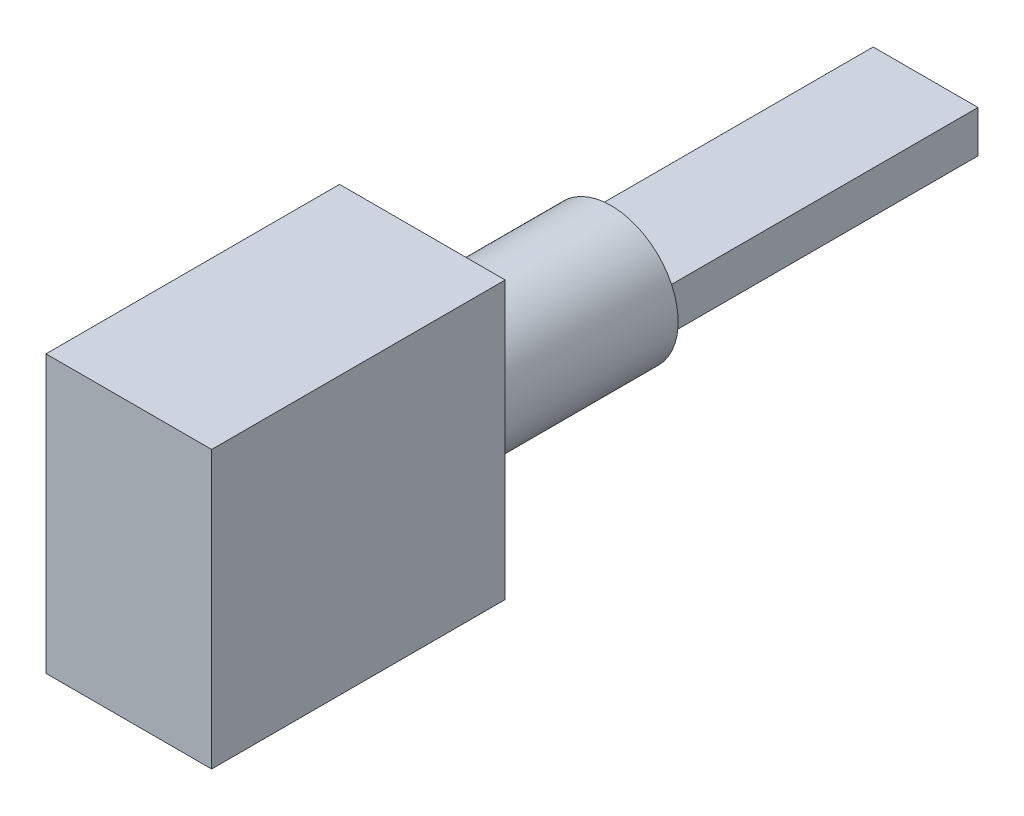
SolidWorks part; units mm, degrees
ref_plane "前基準面" through (0, 0, 0) normal (0, 0, 1) x (1, 0, 0)
ref_plane "上基準面" through (0, 0, 0) normal (0, 1, 0) x (1, 0, 0)
ref_plane "右基準面" through (0, 0, 0) normal (1, 0, 0) x (0, 0, -1)
sketch "草圖1" plane through (0, 0, 0) normal (0, 0, 1) x (1, 0, 0)
  line L0 (-43.8655, -29.1074) -> (43.7345, -29.1074) construction
  line L1 (-24.6655, -72.3074) -> (-32.5655, -72.3074)
  line L2 (-24.6655, -72.3074) -> (-24.6655, -59.1074)
  line L3 (-24.6655, -59.1074) -> (-32.5655, -59.1074)
  line L4 (-32.5655, -72.3074) -> (-32.5655, -59.1074)
  line L5 (-44.5655, -42.9237) -> (-44.5655, -29.8074) construction
  point P6 (-32.5655, -65.7074)
  dimension "D1" = 7.9
  dimension "D2" = 13.2
  dimension "D3" = 30
  dimension "D4" = 12
extrude "填料-伸長1" add sketch "草圖1" along normal blind 14
sketch "草圖2" plane through (0, 0, 0) normal (0, 0, -1) x (-1, 0, 0)
  line L0 (32.5655, -59.1074) -> (32.5655, -72.3074) construction
  line L1 (24.6655, -59.1074) -> (32.5655, -59.1074) construction
  line L2 (24.6655, -72.3074) -> (24.6655, -59.1074) construction
  circle A0 centre (28.6155, -65.7074) radius 3.2
  dimension "D1" = 6.4
  dimension "D2" = 3.95
  dimension "D3" = 6.6
  dimension "D4" = 3.95
extrude "填料-伸長2" add sketch "草圖2" along normal blind 9
sketch "草圖3" plane through (0, 0, -9) normal (0, 0, -1) x (-1, 0, 0)
  line L0 (24.6655, -72.3074) -> (24.6655, -59.1074) construction
  line L1 (26.1155, -64.7074) -> (31.1155, -64.7074)
  line L2 (26.1155, -64.7074) -> (26.1155, -66.7074)
  line L3 (26.1155, -66.7074) -> (31.1155, -66.7074)
  line L4 (31.1155, -64.7074) -> (31.1155, -66.7074)
  line L5 (24.6655, -59.1074) -> (32.5655, -59.1074) construction
  point P4 (28.6155, -64.7074)
  point P7 (31.1155, -65.7074)
  dimension "D1" = 3.95
  dimension "D2" = 6.6
  dimension "D3" = 2
  dimension "D4" = 5
extrude "填料-伸長3" add sketch "草圖3" along normal blind 15
